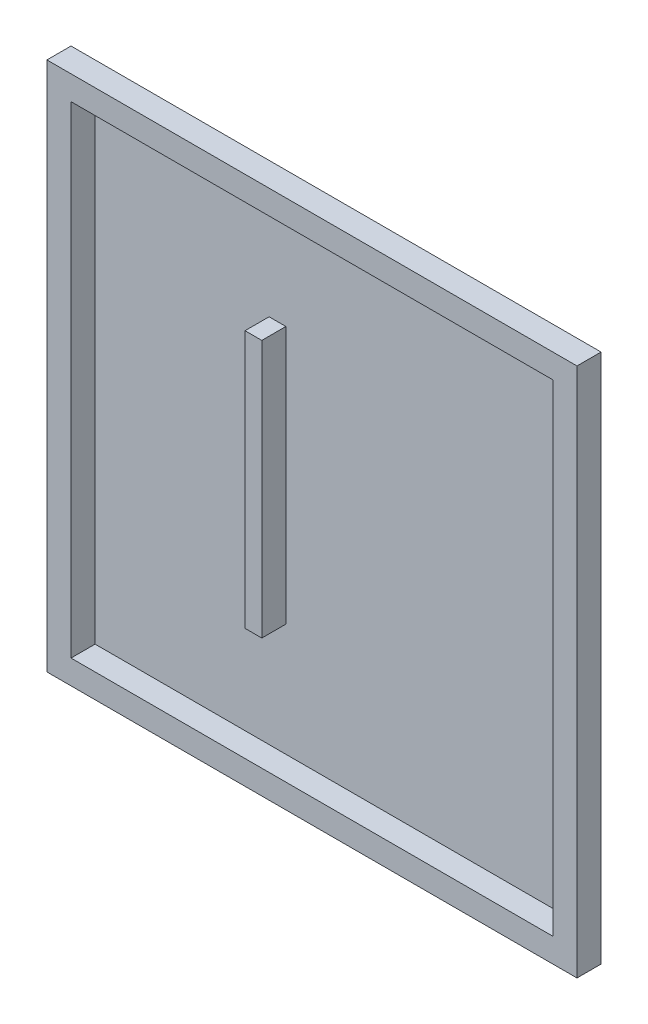
SolidWorks part; units mm, degrees
ref_plane "Płaszczyzna przednia" through (0, 0, 0) normal (0, 0, 1) x (1, 0, 0)
ref_plane "Płaszczyzna górna" through (0, 0, 0) normal (0, 1, 0) x (1, 0, 0)
ref_plane "Płaszczyzna prawa" through (0, 0, 0) normal (1, 0, 0) x (0, 0, -1)
sketch "Szkic1" plane through (0, 0, 0) normal (0, 0, 1) x (1, 0, 0)
  line L1 (-21, 21) -> (-1, 21)
  line L2 (-21, 21) -> (-21, 1)
  line L3 (-21, 1) -> (-1, 1)
  line L4 (-1, 21) -> (-1, 1)
  dimension "D1" = 20
  dimension "D2" = 20
  dimension "D3" = 1
  dimension "D4" = 1
extrude "Dodanie-wyciągnięcie1" add sketch "Szkic1" along normal blind 0.1
sketch "Szkic2" plane through (0, 0, 0.1) normal (0, 0, 1) x (1, 0, 0)
  line L1 (-22, 0) -> (0, 0)
  line L2 (-22, 0) -> (-22, 22)
  line L3 (-22, 22) -> (0, 22)
  line L4 (-21, 21) -> (-21, 1)
  line L5 (-21, 1) -> (-1, 1)
  line L6 (-1, 1) -> (-1, 21)
  line L7 (-1, 21) -> (-21, 21)
  line L8 (-21, 21) -> (-21, 1)
  line L9 (-21, 1) -> (-1, 1)
  line L10 (-1, 1) -> (-1, 21)
  line L11 (-1, 21) -> (-21, 21)
  line L12 (0, 0) -> (0, 22)
  dimension "D2" = 1
  dimension "D3" = 1
  dimension "D4" = 22
  dimension "D5" = 22
  dimension "D1" = 0
extrude "Dodanie-wyciągnięcie2" add sketch "Szkic2" along normal blind 1 separate body
sketch "Szkic3" plane through (0, 0, 0.1) normal (0, 0, 1) x (1, 0, 0)
  line L0 (-1, 1) -> (-1, 21) construction
  line L1 (-13.7786, 5.6787) -> (-13.0819, 5.6787)
  line L2 (-13.7786, 5.6787) -> (-13.7786, 16.3777)
  line L3 (-13.7786, 16.3777) -> (-13.0819, 16.3777)
  line L4 (-13.0819, 5.6787) -> (-13.0819, 16.3777)
  line L5 (-1, 21) -> (-21, 21) construction
  point P4 (-14.2863, 18.6936)
  point P5 (-12.1819, 7.0388)
  point P6 (-12.8786, 15.4777)
  dimension "D1" = 10.699
  dimension "D2" = 0.6967
  dimension "D3" = 12.0819
  dimension "D4" = 4.6223
extrude "Dodanie-wyciągnięcie3" add sketch "Szkic3" along normal blind 1
